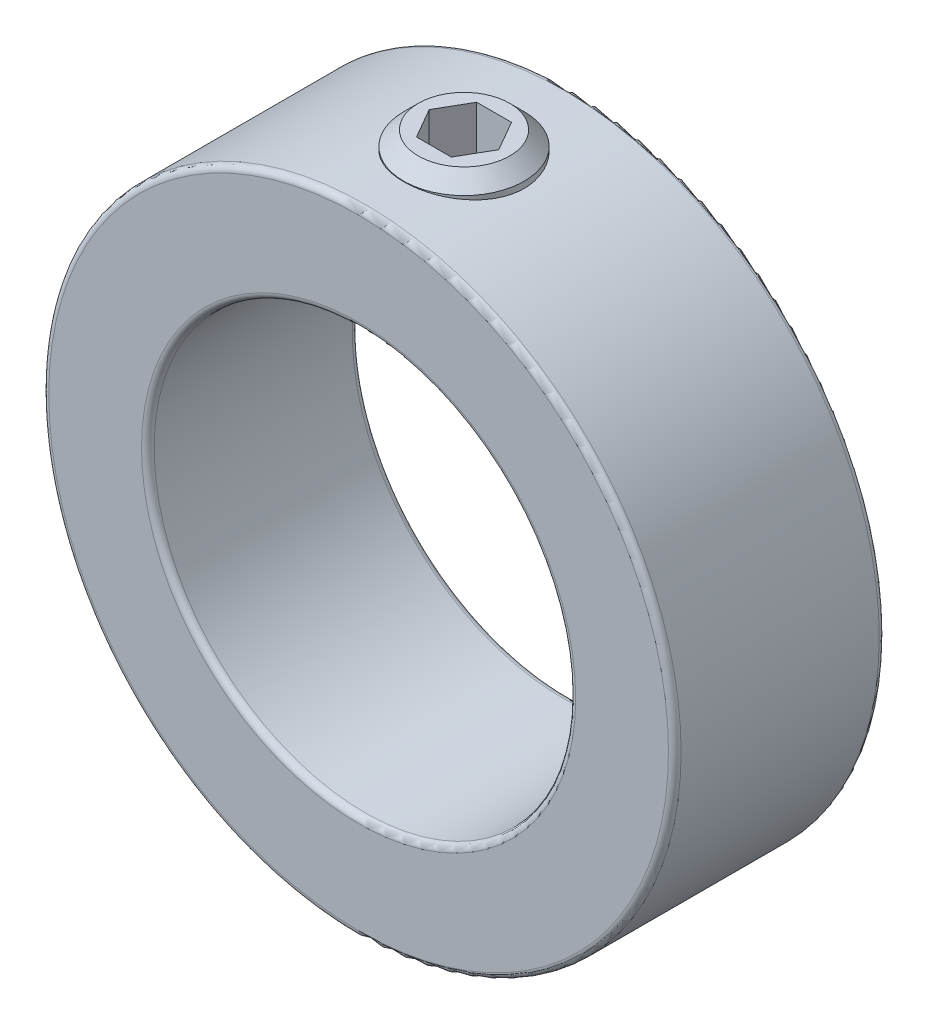
SolidWorks part; units mm, degrees
ref_plane "Front Plane" through (0, 0, 0) normal (0, 0, 1) x (1, 0, 0)
ref_plane "Top Plane" through (0, 0, 0) normal (0, 1, 0) x (1, 0, 0)
ref_plane "Right Plane" through (0, 0, 0) normal (1, 0, 0) x (0, 0, -1)
sketch "Sketch1" plane through (0, 0, 0) normal (0, 0, 1) x (1, 0, 0)
  circle A0 centre (0, 0) radius 33.3375
  circle A1 centre (0, 0) radius 22.225
  point P4 (33.3375, 0)
  dimension "Bore Dia" = 44.45
  dimension "OD" = 66.675
extrude "Extrude1" add sketch "Sketch1" along normal mid plane 22.225
sketch "Sketch2" plane through (41.275, 0, 0) normal (0, -1, 0) x (0, 0, -1)
  line L0 (11.1125, -41.275) -> (-11.1125, -41.275) construction
  line L1 (-11.1125, -7.9375) -> (-11.1125, -74.6125) construction
  line L2 (11.1125, -74.6125) -> (11.1125, -7.9375) construction
  circle A0 centre (0, -41.275) radius 6.35
  point P7 (0, -47.625)
  dimension "Set Screw Dia" = 12.7
extrude "Cut-Extrude1" cut sketch "Sketch2" against normal through all
fillet "Fillet1" radius 0.6667 4 edges at (22.225, 0, -11.1125) (22.225, 0, 11.1125) (33.3375, 0, -11.1125) (33.3375, 0, 11.1125)
sketch "Sketch3" plane through (0, 0, 0) normal (0, 0, 1) x (1, 0, 0)
  line L0 (-4.8164, 22.225) -> (-1.8403, 22.225)
  line L1 (0, 24.0653) -> (-1.8403, 22.225)
  line L2 (0, 24.0653) -> (0, 34.925)
  line L3 (0, 34.925) -> (-4.8164, 34.925)
  line L4 (-6.35, 23.7586) -> (-6.35, 33.3914)
  line L5 (0, 22.225) -> (0, 0) construction
  line L6 (-6.35, 23.7586) -> (-6.35, 22.225) construction
  line L7 (-6.35, 22.225) -> (-4.8164, 22.225) construction
  line L8 (-6.35, 33.3914) -> (-6.35, 34.925) construction
  line L9 (-4.8164, 22.225) -> (-6.35, 23.7586)
  line L10 (-6.35, 33.3914) -> (-4.8164, 34.925)
  line L11 (-6.35, 34.925) -> (-4.8164, 34.925) construction
  line L12 (-1.8403, 22.225) -> (0, 22.225) construction
  line L13 (0, 22.225) -> (0, 24.0653) construction
  circle A1 centre (0, 0) radius 22.225 construction
  dimension "Screw Length" = 12.7
  dimension "D2" = 1.5336
  dimension "D1" = 1.8403
revolve "Revolve1" add sketch "Sketch3" angle 360 about L5
sketch "Sketch4" plane through (3.3734, 34.925, 0) normal (0, -1, 0) x (0, 0, -1)
  line L1 (0, 0.2927) -> (-3.175, -1.5404)
  line L2 (-3.175, -1.5404) -> (-3.175, -5.2065)
  line L3 (-3.175, -5.2065) -> (0, -7.0396)
  line L4 (0, -7.0396) -> (3.175, -5.2065)
  line L5 (3.175, -5.2065) -> (3.175, -1.5404)
  line L6 (3.175, -1.5404) -> (0, 0.2927)
  circle A0 centre (0, -3.3734) radius 3.175 construction
  circle A1 centre (0, -3.3734) radius 3.6662 construction
  dimension "D1" = 7.3323
  dimension "Hex Size" = 6.35
extrude "Cut-Extrude2" cut sketch "Sketch4" along normal blind 6.35
equation "\"D1@Fillet1\" = \"OD@Sketch1\"*.01"
equation "\"D1@Cut-Extrude2\" = \"Hex Size@Sketch4\""
equation "\"D2@Sketch3\" =(\"Set Screw Dia@Sketch2\"-\"D1@Sketch4\")/3.5"
equation "\"D1@Sketch3\" = \"D2@Sketch3\"*1.2"
